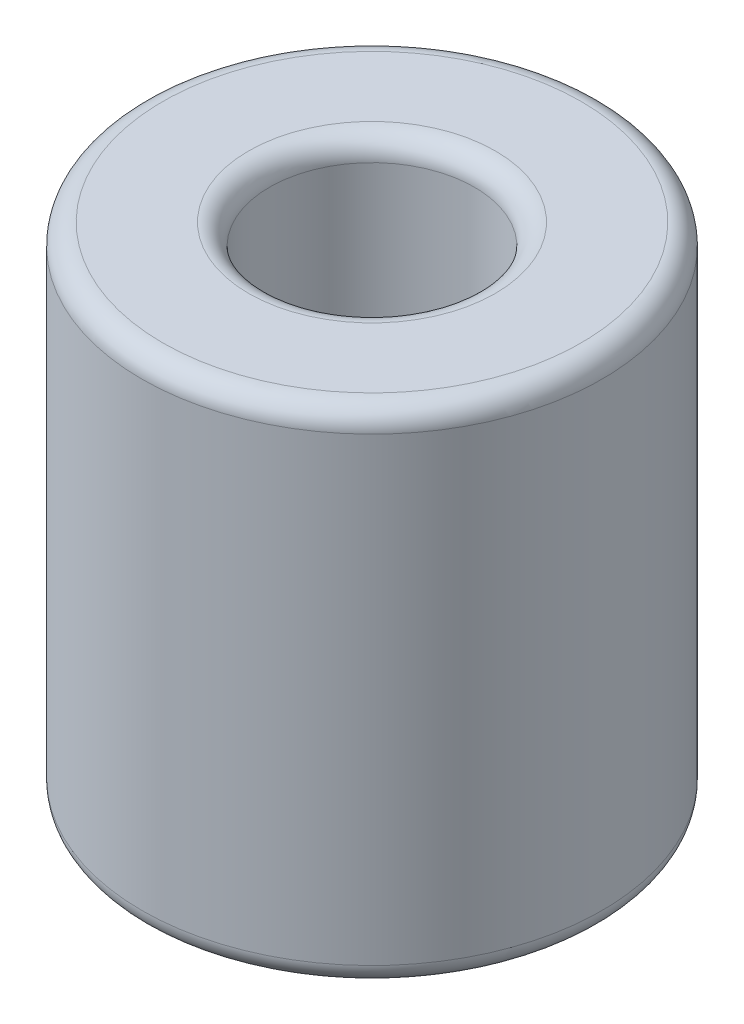
SolidWorks part; units mm, degrees
ref_plane "Front Plane" through (0, 0, 0) normal (0, 0, 1) x (1, 0, 0)
ref_plane "Top Plane" through (0, 0, 0) normal (0, 1, 0) x (1, 0, 0)
ref_plane "Right Plane" through (0, 0, 0) normal (1, 0, 0) x (0, 0, -1)
sketch "Sketch1" plane through (0, 0, 0) normal (0, 1, 0) x (1, 0, 0)
  circle A0 centre (0, 0) radius 5.5
  circle A1 centre (0, 0) radius 2.45
extrude "Boss-Extrude1" add sketch "Sketch1" along normal blind 12
fillet "Fillet1" radius 0.5 4 edges at (0, 0, 2.45) (0, 0, 5.5) (0, 12, 5.5) (0, 12, 2.45)
